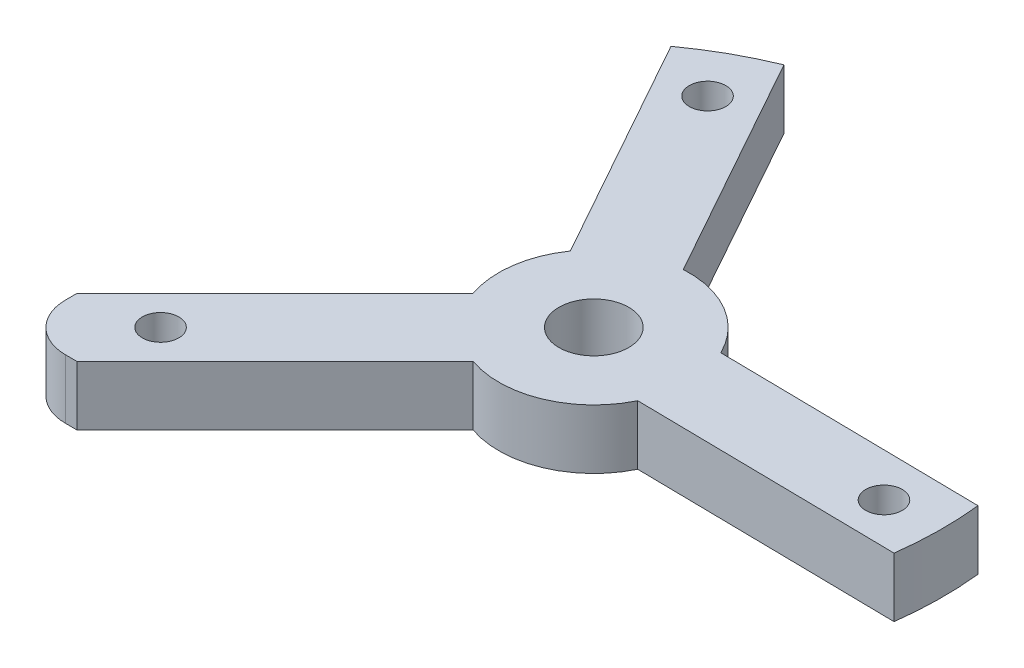
SolidWorks part; units mm, degrees
material "ABS"
ref_plane "Front Plane" through (0, 0, 0) normal (0, 0, 1) x (1, 0, 0)
ref_plane "Top Plane" through (0, 0, 0) normal (0, 1, 0) x (1, 0, 0)
ref_plane "Right Plane" through (0, 0, 0) normal (1, 0, 0) x (0, 0, -1)
sketch "Sketch2" plane through (0, 0, 0) normal (0, 1, 0) x (1, 0, 0)
  line L0 (57.0914, -86.9174) -> (83.572, -60.4367)
  line L1 (99.1458, -53.9863) -> (133.9172, -54.4991)
  line L4 (87.7236, -48.4345) -> (58.7657, -77.3924) construction
  line L5 (87.7236, -48.4345) -> (68.5436, -14.0525) construction
  line L6 (87.7236, -48.4345) -> (127.0893, -49.015) construction
  line L7 (99.1458, -42.8826) -> (134.0405, -43.3972)
  line L8 (75.7214, -52.586) -> (49.2407, -79.0667)
  line L9 (127.0893, -49.015) -> (127.0893, -43.2947) construction
  line L10 (127.0893, -49.015) -> (127.0893, -43.2947) construction
  line L11 (99.1458, -42.8826) -> (100.4236, -48.4345) construction
  line L12 (100.4236, -48.4345) -> (99.1458, -53.9863) construction
  line L13 (87.0068, -35.7547) -> (70.0358, -5.3327)
  line L14 (60.3399, -10.7415) -> (77.3109, -41.1636)
  line L15 (77.3109, -41.1636) -> (81.5365, -37.3435) construction
  line L16 (49.2407, -22.1725) -> (49.2407, -80.5674) construction
  line L17 (81.5365, -37.3435) -> (87.0068, -35.7547) construction
  line L18 (55.5907, -86.9174) -> (113.9855, -86.9174) construction
  line L19 (49.2407, -79.0667) -> (49.2407, -80.5674)
  line L20 (55.5907, -86.9174) -> (57.0914, -86.9174)
  circle A1 centre (87.7236, -48.4345) radius 4.6672
  circle A2 centre (87.7236, -48.4345) radius 12.7
  circle A3 centre (127.0893, -49.015) radius 2.4384
  circle A4 centre (58.7657, -77.3924) radius 2.4384
  circle A5 centre (68.5436, -14.0525) radius 2.4384
  circle A7 centre (127.0893, -49.015) radius 2.4574 construction
  arc A8 (49.2407, -80.5674) -> (55.5907, -86.9174) centre (55.5907, -80.5674) ccw construction
  arc A9 (49.2407, -80.5674) -> (55.5907, -86.9174) centre (55.5907, -80.5674) ccw
  arc A11 (92.9606, -2.1398) -> (49.2407, -22.1725) centre (87.7236, -48.4345) ccw construction
  arc A12 (113.9855, -86.9174) -> (134.0183, -43.1975) centre (87.7236, -48.4345) ccw construction
  circle A13 centre (87.7236, -48.4345) radius 6.35 construction
  arc A14 (70.0358, -5.3327) -> (60.3399, -10.7415) centre (87.7236, -48.4345) ccw
  arc A15 (133.9172, -54.4991) -> (134.0405, -43.3972) centre (87.7236, -48.4345) ccw
  circle A16 centre (68.5436, -14.0525) radius 2.4574 construction
  circle A17 centre (58.7657, -77.3924) radius 2.4574 construction
  point P8 (0, 0)
  point P9 (73.4873, -11.099)
  point P15 (0, 0)
  point P20 (-22.2749, -36.5912)
  point P30 (0, 0)
  point P39 (0, 0)
  point P42 (0, 0)
  point P50 (0, 0)
  dimension "D2" = 9.3345
  dimension "D7" = 25.4
  dimension "D10" = 4.8768
  dimension "D3" = 11.1025
  dimension "D4" = 11.1025
  dimension "D5" = 11.1025
extrude "Boss-Extrude1" add sketch "Sketch2" along normal blind 7.9375
